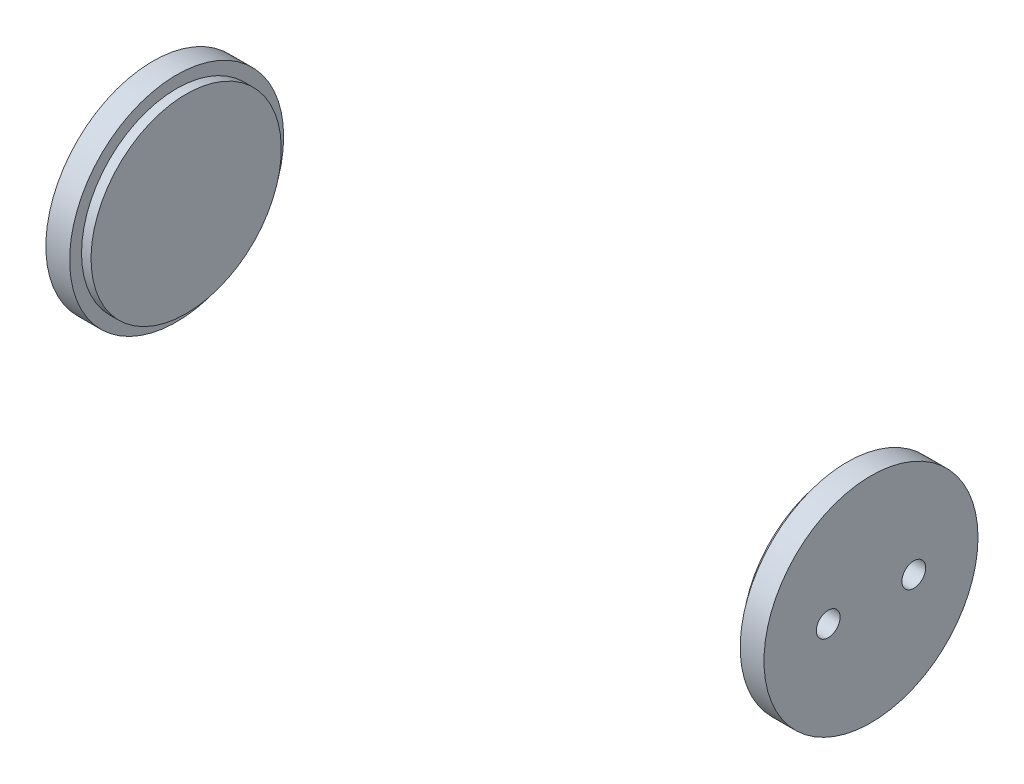
SolidWorks part; units mm, degrees
ref_plane "Front Plane" through (0, 0, 0) normal (0, 0, 1) x (1, 0, 0)
ref_plane "Top Plane" through (0, 0, 0) normal (0, 1, 0) x (1, 0, 0)
ref_plane "Right Plane" through (0, 0, 0) normal (1, 0, 0) x (0, 0, -1)
sketch "Sketch1" plane through (0, 0, 0) normal (1, 0, 0) x (0, 0, -1)
  circle A0 centre (0, 0) radius 22.5
  dimension "D1" = 45
extrude "Boss-Extrude1" add sketch "Sketch1" along normal mid plane 5
sketch "Sketch2" plane through (2.5, 0, 0) normal (1, 0, 0) x (0, 0, -1)
  circle A0 centre (0, 0) radius 20
  dimension "D1" = 40
extrude "Boss-Extrude2" add sketch "Sketch2" along normal blind 2
sketch "Sketch3" plane through (4.5, 0, 0) normal (1, 0, 0) x (0, 0, -1)
  circle A0 centre (0, 0) radius 22.5
extrude "Boss-Extrude3" add sketch "Sketch3" along normal blind 66
sketch "Sketch4" plane through (70.5, 0, 0) normal (1, 0, 0) x (0, 0, -1)
  circle A0 centre (0, 0) radius 12.5
  dimension "D1" = 25
extrude "Boss-Extrude4" add sketch "Sketch4" along normal blind 5
sketch "Sketch5" plane through (75.5, 0, 0) normal (1, 0, 0) x (0, 0, -1)
  circle A0 centre (0, 0) radius 22.5
  dimension "D1" = 45
extrude "Boss-Extrude5" add sketch "Sketch5" along normal blind 66
sketch "Sketch6" plane through (141.5, 0, 0) normal (1, 0, 0) x (0, 0, -1)
  circle A0 centre (0, 0) radius 20
  dimension "D1" = 40
extrude "Boss-Extrude6" add sketch "Sketch6" along normal blind 2
sketch "Sketch7" plane through (143.5, 0, 0) normal (1, 0, 0) x (0, 0, -1)
  circle A0 centre (0, 0) radius 22.5
  dimension "D1" = 45
extrude "Boss-Extrude7" add sketch "Sketch7" along normal blind 5
sketch "Sketch8" plane through (148.5, 0, 0) normal (1, 0, 0) x (0, 0, -1)
  line L0 (-9, 0) -> (9, 0) construction
  circle A0 centre (0, 0) radius 22.5 construction
  circle A2 centre (-9, 0) radius 2.5
  circle A3 centre (9, 0) radius 2.5
  dimension "D1" = 5
  dimension "D2" = 9
  dimension "D3" = 9
extrude "Cut-Extrude1" cut sketch "Sketch8" against normal blind 5
sketch "Sketch9" plane through (-2.5, 0, 0) normal (-1, 0, 0) x (0, 0, 1)
  circle A1 centre (-9, 0) radius 2.5
  circle A2 centre (-9, 0) radius 2.5
  circle A3 centre (9, 0) radius 2.5
  circle A4 centre (9, 0) radius 2.5
  dimension "D1" = 0
  dimension "D2" = 0
extrude "Cut-Extrude2" cut sketch "Sketch9" against normal blind 5
sketch "Sketch10" plane through (0, 0, 0) normal (0, 0, 1) x (1, 0, 0)
  line L1 (4.5, 22.5) -> (141.5, 22.5)
  line L2 (4.5, 22.5) -> (4.5, -22.5)
  line L3 (4.5, -22.5) -> (141.5, -22.5)
  line L4 (141.5, 22.5) -> (141.5, -22.5)
extrude "Cut-Extrude4" cut sketch "Sketch10" against normal mid plane 64
